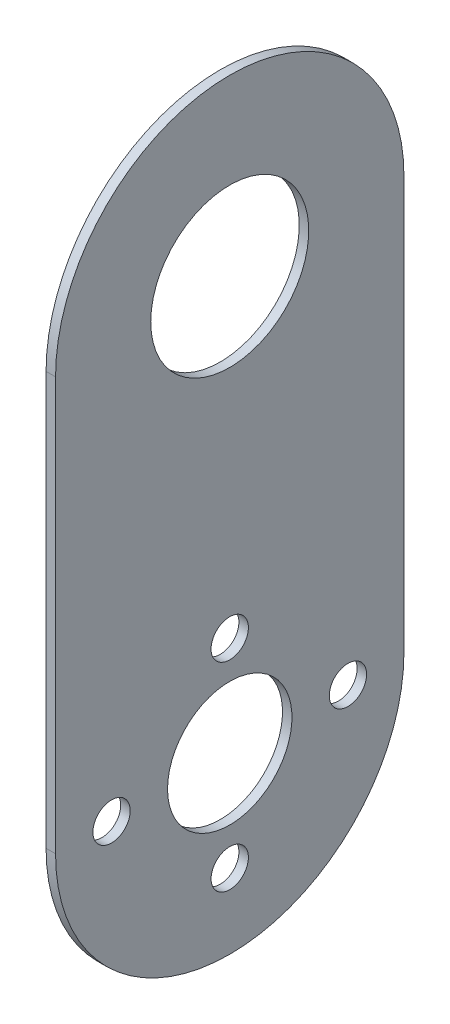
SolidWorks part; units mm, degrees
material "AISI 1020"
ref_plane "Front Plane" through (0, 0, 0) normal (0, 0, 1) x (1, 0, 0)
ref_plane "Top Plane" through (0, 0, 0) normal (0, 1, 0) x (1, 0, 0)
ref_plane "Right Plane" through (0, 0, 0) normal (1, 0, 0) x (0, 0, -1)
sketch "Sketch1" plane through (0, 0, 0) normal (1, 0, 0) x (0, 0, -1)
  line L0 (-6.35, 0) -> (6.35, 0) construction
  line L4 (14.0005, 0) -> (14.0005, -33.1978)
  line L5 (-14.0005, 0) -> (-14.0005, -33.1978)
  circle A0 centre (0, 0) radius 6.35
  arc A1 (-14.0005, -33.1978) -> (14.0005, -33.1978) centre (0, -33.1978) ccw
  arc A2 (14.0005, 0) -> (-14.0005, 0) centre (0, 0) ccw
  circle A3 centre (0, -25.1978) radius 1.5
  circle A4 centre (0, -41.1978) radius 1.5
  circle A5 centre (-9.5, -33.1978) radius 1.5
  circle A6 centre (9.5, -33.1978) radius 1.5
  circle A7 centre (0, -33.1978) radius 5
  dimension "D1" = 12.7
  dimension "D2" = 33.1978
  dimension "D3" = 28.001
  dimension "D4" = 19
  dimension "D8" = 3
  dimension "D9" = 10
  dimension "D5" = 9.5
  dimension "D6" = 8
  dimension "D7" = 16
extrude "Boss-Extrude1" add sketch "Sketch1" along normal blind 0.762
